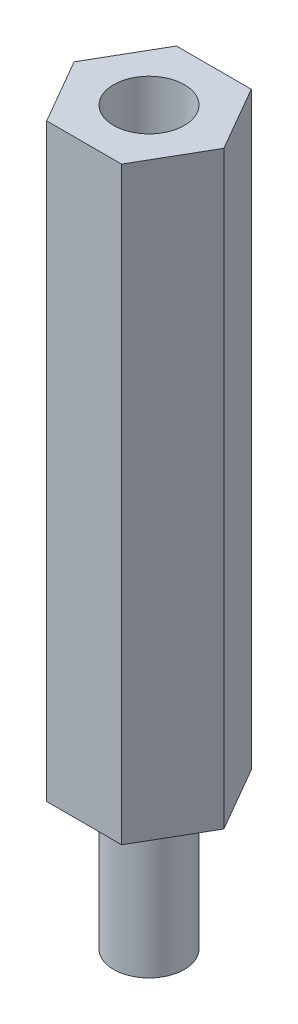
SolidWorks part; units mm, degrees
material "Plain Carbon Steel"
ref_plane "Front Plane" through (0, 0, 0) normal (0, 0, 1) x (1, 0, 0)
ref_plane "Top Plane" through (0, 0, 0) normal (0, 1, 0) x (1, 0, 0)
ref_plane "Right Plane" through (0, 0, 0) normal (1, 0, 0) x (0, 0, -1)
sketch "Sketch1" plane through (0, 0, 0) normal (0, 1, 0) x (1, 0, 0)
  line L1 (3.1754, 0) -> (1.5877, 2.75)
  line L2 (1.5877, 2.75) -> (-1.5877, 2.75)
  line L3 (-1.5877, 2.75) -> (-3.1754, 0)
  line L4 (-3.1754, 0) -> (-1.5877, -2.75)
  line L5 (-1.5877, -2.75) -> (1.5877, -2.75)
  line L6 (1.5877, -2.75) -> (3.1754, 0)
  circle A0 centre (0, 0) radius 2.75 construction
  dimension "D1" = 5.5
extrude "Boss-Extrude1" add sketch "Sketch1" along normal blind 25
sketch "Sketch2" plane through (0, 25, 0) normal (0, 1, 0) x (1, 0, 0)
  circle A0 centre (0, 0) radius 1.5
  dimension "D1" = 3
extrude "Cut-Extrude1" cut sketch "Sketch2" against normal blind 12
sketch "Sketch3" plane through (0, 0, 0) normal (0, -1, 0) x (-1, 0, 0)
  circle A0 centre (0, 0) radius 1.5
  point P3 (-0.9467, 0.575)
extrude "Boss-Extrude2" add sketch "Sketch3" along normal blind 6
